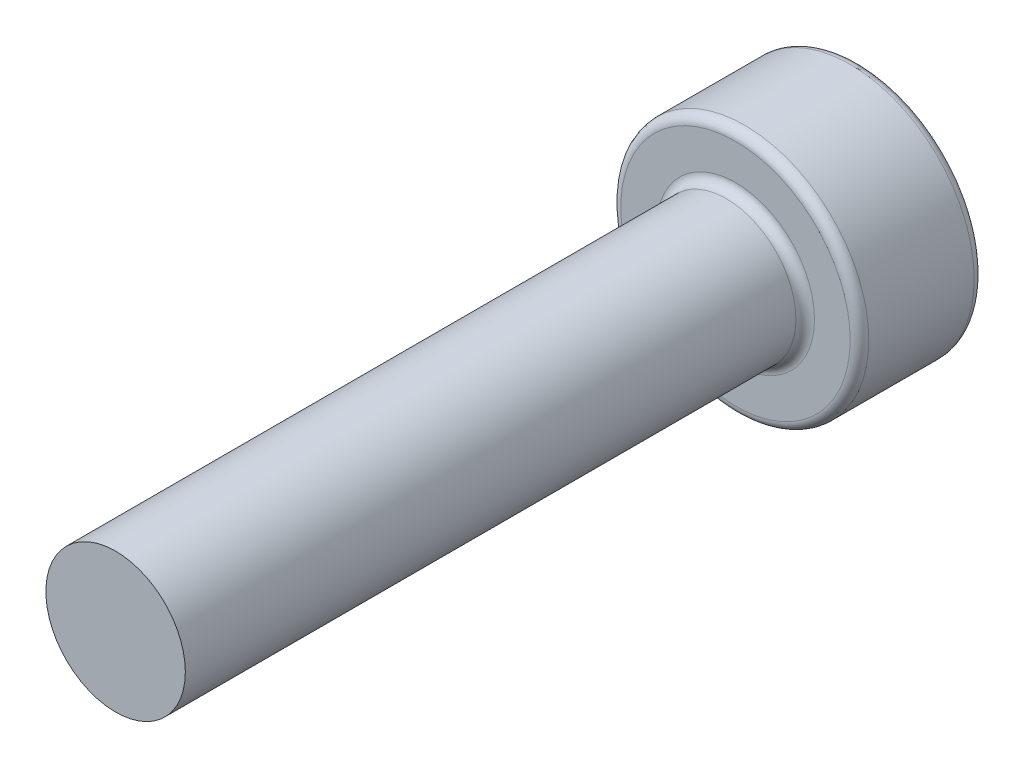
SolidWorks part; units mm, degrees
material "1.4031(X39Cr13)"
ref_plane "Ebene vorne" through (0, 0, 0) normal (0, 0, 1) x (1, 0, 0)
ref_plane "Ebene oben" through (0, 0, 0) normal (0, 1, 0) x (1, 0, 0)
ref_plane "Ebene rechts" through (0, 0, 0) normal (1, 0, 0) x (0, 0, -1)
sketch "Skizze1" plane through (0, 0, 0) normal (0, 1, 0) x (0, 0, -1)
  line L0 (0, 0) -> (0, 24)
  line L1 (0, 24) -> (4, 24)
  line L2 (4, 24) -> (4, 20)
  line L3 (4, 20) -> (2.25, 20)
  line L4 (2.25, 20) -> (2.25, 0)
  line L5 (2.25, 0) -> (0, 0)
  dimension "D1" = 20
  dimension "D2" = 2.25
  dimension "D3" = 4
  dimension "D4" = 4
revolve "Rotation1" add sketch "Skizze1" angle 360 about L0
sketch "Skizze2" plane through (-24, 0, 0) normal (-1, 0, 0) x (0, 1, 0)
  line L1 (0, 2.8868) -> (-2.5, 1.4434)
  line L2 (-2.5, 1.4434) -> (-2.5, -1.4434)
  line L3 (-2.5, -1.4434) -> (0, -2.8868)
  line L4 (0, -2.8868) -> (2.5, -1.4434)
  line L5 (2.5, -1.4434) -> (2.5, 1.4434)
  line L6 (2.5, 1.4434) -> (0, 2.8868)
  circle A0 centre (0, 0) radius 2.5 construction
  dimension "D1" = 5
extrude "Schnitt-Linear austragen1" cut sketch "Skizze2" against normal blind 3
fillet "Verrundung1" radius 0.3 3 edges at (-20, 0, -2.25) (-20, 0, -4) (-24, 0, -4)
sketch "Skizze4" plane through (0, 0, 0) normal (0, 0, 1) x (1, 0, 0)
  line L0 (0, 0) -> (0, 12.1914)
pattern_circular "Kreismuster1" count 2 every 90 about axis through (0, 0, 0) along (0, 1, 0) of bodies 102
delete or keep bodies "Körper-Löschen/beibehalten 1" type delete bodies bodies 102
